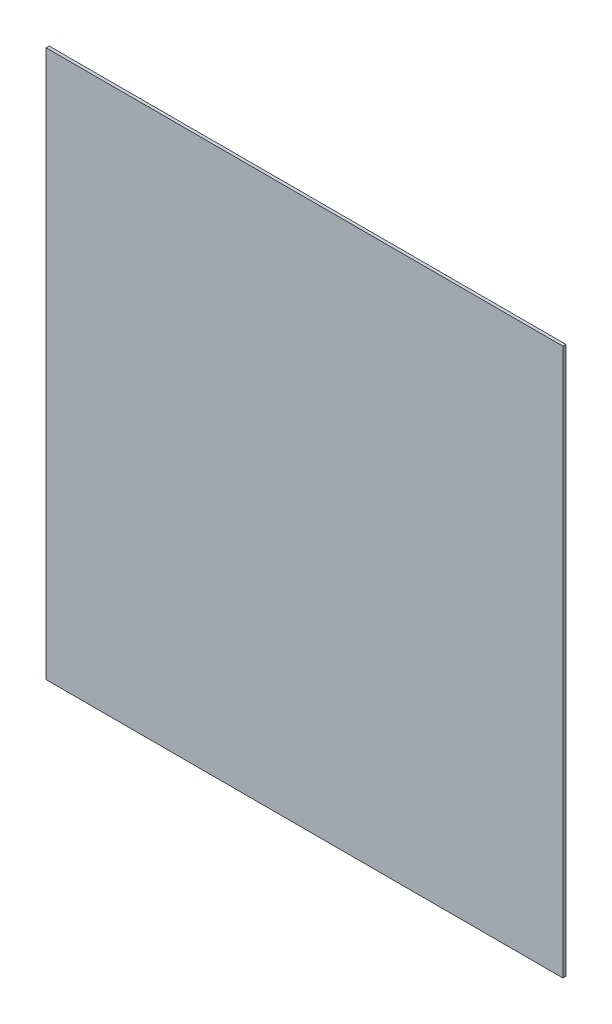
SolidWorks part; units mm, degrees
ref_plane "Front Plane" through (0, 0, 0) normal (0, 0, 1) x (1, 0, 0)
ref_plane "Top Plane" through (0, 0, 0) normal (0, 1, 0) x (1, 0, 0)
ref_plane "Right Plane" through (0, 0, 0) normal (1, 0, 0) x (0, 0, -1)
sketch "Sketch1" plane through (0, 0, 0) normal (0, 0, 1) x (1, 0, 0)
  line L1 (255, -270) -> (-255, -270)
  line L2 (255, -270) -> (255, 270)
  line L3 (255, 270) -> (-255, 270)
  line L4 (-255, -270) -> (-255, 270)
  line L5 (255, -270) -> (-255, 270) construction
  line L6 (255, 270) -> (-255, -270) construction
  point P0 (0, 0)
  dimension "D1" = 510
  dimension "D2" = 540
extrude "Boss-Extrude1" add sketch "Sketch1" along normal blind 3
